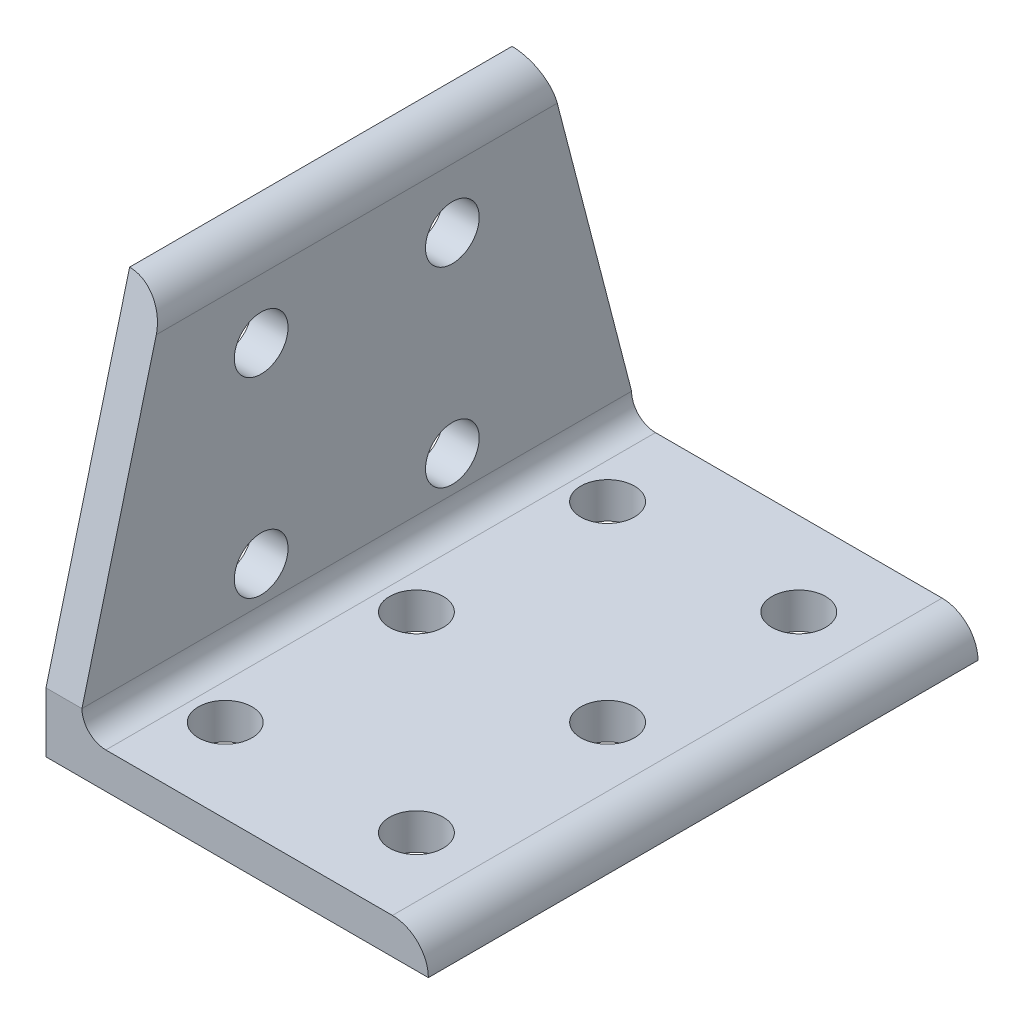
SolidWorks part; units mm, degrees
ref_plane "Front Plane" through (0, 0, 0) normal (0, 0, 1) x (1, 0, 0)
ref_plane "Top Plane" through (0, 0, 0) normal (0, 1, 0) x (1, 0, 0)
ref_plane "Right Plane" through (0, 0, 0) normal (1, 0, 0) x (0, 0, -1)
sketch "Sketch1" plane through (0, 0, 0) normal (0, 0, 1) x (1, 0, 0)
  line L0 (25.4, -25.4) -> (-25.4, -25.4) construction
  line L1 (-25.4, 25.4) -> (-25.4, -25.4) construction
  line L2 (25.4, -25.4) -> (25.4, -20.6248) construction
  point P3 (0, -25.4)
  point P6 (-25.4, 0)
  dimension "Length" = 50.8
  dimension "Thickness" = 4.7752
sketch "Sketch2" plane through (0, 0, 0) normal (1, 0, 0) x (0, 0, -1)
  line L0 (36.5125, 0) -> (-36.5125, 0) construction
  line L1 (-25.4, 25.4) -> (25.4, 25.4) construction
  line L2 (0, 25.4) -> (0, -25.4) construction
  line L3 (0, 25.4) -> (0, -25.4) construction
  line L4 (-12.7, 16.2687) -> (-12.7, 9.1313) construction
  line L5 (-12.7, 12.7) -> (0, 0) construction
  point P4 (0, 0)
  point P13 (0, 25.4)
  point P16 (-12.7, 12.7)
  dimension "Width" = 73.025
  dimension "Top Width" = 50.8
  dimension "Hole Spacing" = 25.4
  dimension "Hole Dia" = 7.1374
  dimension "D1" = 45
sketch "Sketch3" plane through (0, 0, 0) normal (0, 1, 0) x (1, 0, 0)
  line L0 (0, 36.5125) -> (0, -36.5125) construction
  line L1 (0, 36.5125) -> (0, -36.5125) construction
  line L2 (25.4, 0) -> (-25.4, 0) construction
  line L3 (25.4, 0) -> (-25.4, 0) construction
  point P4 (-12.7, 0)
  dimension "D1" = 25.4
sketch "Sketch4" plane through (0, 0, 0) normal (0, 0, 1) x (1, 0, 0)
  line L0 (-25.4, 25.4) -> (-25.4, -25.4)
  line L1 (-25.4, -25.4) -> (25.4, -25.4)
  line L2 (-20.6248, 20.6248) -> (-20.6248, -17.4498)
  line L3 (-17.4498, -20.6248) -> (20.6248, -20.6248)
  arc A0 (-20.6248, -17.4498) -> (-17.4498, -20.6248) centre (-17.4498, -17.4498) ccw
  arc A1 (20.6248, -20.6248) -> (25.4, -25.4) centre (20.6248, -25.4) cw
  arc A2 (-20.6248, 20.6248) -> (-25.4, 25.4) centre (-25.4, 20.6248) ccw
  dimension "Radius" = 3.175
extrude "Boss-Extrude1" add sketch "Sketch4" against normal up to vertex (36.5125 mm away) and the other way up to vertex (36.5125 mm away) up to point (0, 0, -36.5125) other way up to point (0, 0, 36.5125)
sketch "Sketch5" plane through (-20.6248, 0, 0) normal (1, 0, 0) x (0, 0, -1)
  line L0 (-36.5125, -17.4498) -> (-25.4, 25.4)
  line L1 (36.5125, 25.4) -> (-36.5125, 25.4) construction
  line L3 (0, 25.4) -> (0, -25.4) construction
  line L4 (0, 25.4) -> (0, -25.4) construction
  line L6 (-36.5125, -17.4498) -> (-36.5125, 25.4)
  line L7 (-36.5125, 25.4) -> (-25.4, 25.4)
  line L11 (36.5125, 25.4) -> (25.4, 25.4)
  line L12 (36.5125, -17.4498) -> (36.5125, 25.4)
  line L13 (36.5125, -17.4498) -> (25.4, 25.4)
  dimension "D1" = 50.8
extrude "Cut-Extrude1" cut sketch "Sketch5" against normal through all both and the other way through all
sketch "Sketch6" plane through (-20.6248, 0, 0) normal (1, 0, 0) x (0, 0, -1)
  line L0 (-12.7, 16.2687) -> (-12.7, 9.1313) construction
  line L1 (0, 25.4) -> (0, -25.4) construction
  line L2 (0, 25.4) -> (0, -25.4) construction
  line L3 (36.5125, 0) -> (-36.5125, 0) construction
  line L4 (36.5125, 0) -> (-36.5125, 0) construction
  circle A0 centre (-12.7, 12.7) radius 3.5687
  circle A1 centre (-12.7, -12.7) radius 3.5687
  circle A2 centre (12.7, -12.7) radius 3.5687
  circle A3 centre (12.7, 12.7) radius 3.5687
extrude "Cut-Extrude2" cut sketch "Sketch6" against normal through all both and the other way through all
sketch "Sketch7" plane through (0, -20.6248, 0) normal (0, 1, 0) x (1, 0, 0)
  line L0 (0, 36.5125) -> (0, -36.5125) construction
  line L1 (0, 36.5125) -> (0, -36.5125) construction
  line L2 (25.4, 0) -> (-25.4, 0) construction
  line L3 (25.4, 0) -> (-25.4, 0) construction
  circle A0 centre (-12.7, 0) radius 3.5687
  circle A1 centre (-12.7, 25.4) radius 3.5687
  circle A2 centre (-12.7, -25.4) radius 3.5687
  circle A3 centre (12.7, -25.4) radius 3.5687
  circle A4 centre (12.7, 25.4) radius 3.5687
  circle A5 centre (12.7, 0) radius 3.5687
  dimension "D1" = 7.1374
  dimension "D2" = 25.4
extrude "Cut-Extrude3" cut sketch "Sketch7" against normal through all
equation "\"D1@Sketch3\" = \"Hole Spacing@Sketch2\""
equation "\"D1@Sketch7\"=\"Hole Dia@Sketch2\""
equation "\"D2@Sketch7\"=\"Hole Spacing@Sketch2\""
